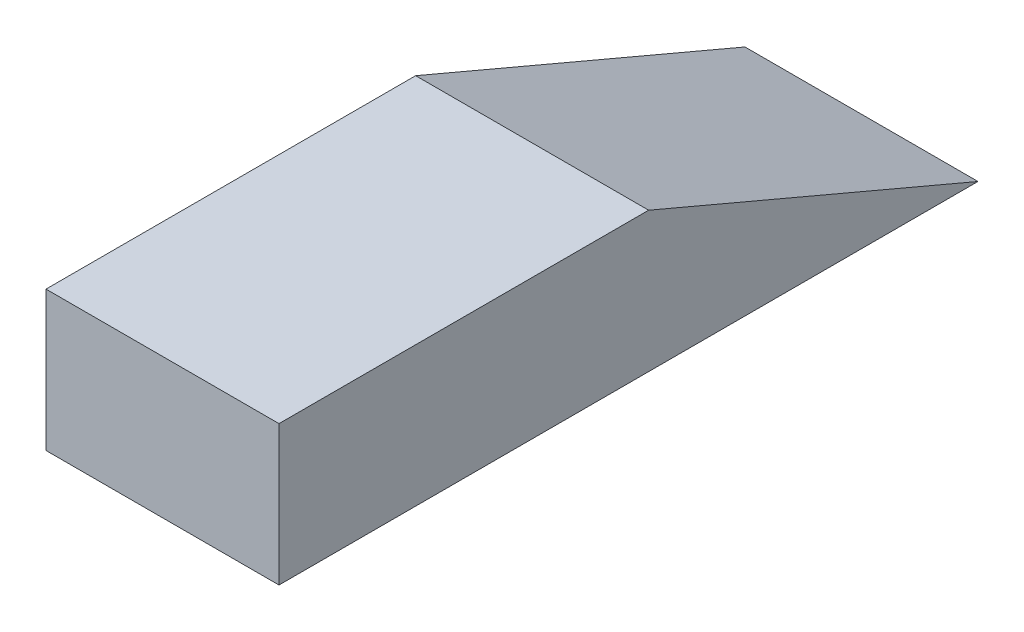
SolidWorks part; units mm, degrees
ref_plane "Front Plane" through (0, 0, 0) normal (0, 0, 1) x (1, 0, 0)
ref_plane "Top Plane" through (0, 0, 0) normal (0, 1, 0) x (1, 0, 0)
ref_plane "Right Plane" through (0, 0, 0) normal (1, 0, 0) x (0, 0, -1)
sketch "Sketch1" plane through (0, 0, 0) normal (0, 0, 1) x (1, 0, 0)
  line L1 (-25, 15) -> (25, 15)
  line L2 (-25, 15) -> (-25, -15)
  line L3 (-25, -15) -> (25, -15)
  line L4 (25, 15) -> (25, -15)
  line L5 (-25, 15) -> (25, -15) construction
  line L6 (-25, -15) -> (25, 15) construction
  point P0 (0, 0)
  dimension "D1" = 50
  dimension "D2" = 30
extrude "Boss-Extrude1" add sketch "Sketch1" along normal blind 150
sketch "Sketch2" plane through (25, 0, 0) normal (1, 0, 0) x (0, 0, -1)
  line L0 (0, -15) -> (-70.6756, 15)
  line L1 (-150, 15) -> (0, 15) construction
  line L2 (-70.6756, 15) -> (0, 15)
  line L3 (0, 15) -> (0, -15)
  dimension "D1" = 67
extrude "Cut-Extrude1" cut sketch "Sketch2" against normal through all
